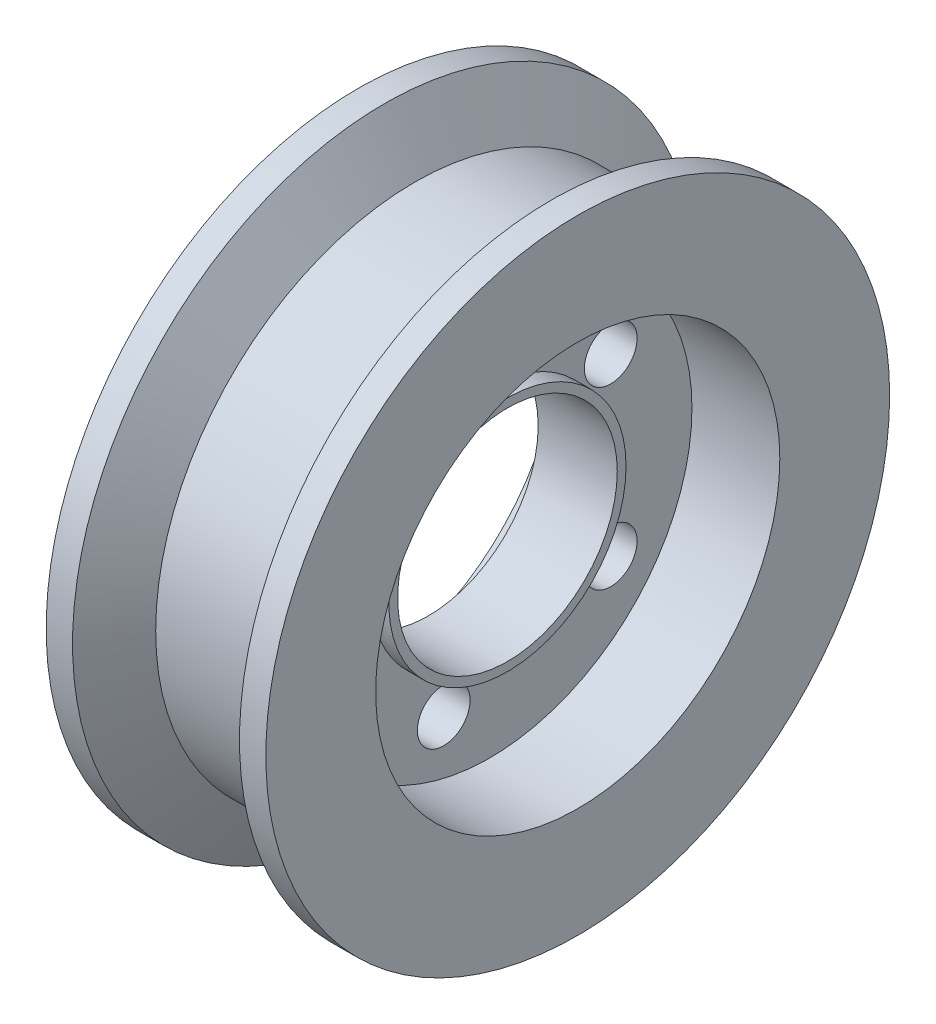
SolidWorks part; units mm, degrees
ref_plane "Front Plane" through (0, 0, 0) normal (1, 0, 0) x (0, 1, 0)
ref_plane "Top Plane" through (0, 0, 0) normal (0, 0, 1) x (0, 1, 0)
ref_plane "Right Plane" through (0, 0, 0) normal (0, 1, 0) x (-1, 0, 0)
sketch "Sketch2" plane through (0, 0, 0) normal (1, 0, 0) x (0, 1, 0)
  circle A0 centre (0, 0) radius 35.5
  circle A1 centre (0, 0) radius 12.5
  dimension "D1" = 71
  dimension "D2" = 25
extrude "Boss-Extrude1" add sketch "Sketch2" along normal mid plane 25 contours A0 A1
sketch "Sketch4" plane through (12.5, 0, 0) normal (1, 0, 0) x (0, 1, 0)
  circle A0 centre (0, 0) radius 23
  circle A1 centre (0, 0) radius 35.5 construction
  dimension "D1" = 12.5
extrude "Cut-Extrude1" cut sketch "Sketch4" against normal blind 10 contours A0
mirror "Mirror1" about plane through (0, 0, 0) normal (1, 0, 0) of "Cut-Extrude1"
sketch "Sketch5" plane through (2.5, 0, 0) normal (1, 0, 0) x (0, 1, 0)
  circle A0 centre (0, 17) radius 3
  dimension "D1" = 6
  dimension "D2" = 17
extrude "Cut-Extrude2" cut sketch "Sketch5" against normal through all
pattern_circular "CirPattern1" count 5 over 360 about axis through (0, 0, 0) along (1, 0, 0) of "Cut-Extrude2"
sketch "Sketch6" plane through (2.5, 0, 0) normal (1, 0, 0) x (0, 1, 0)
  circle A0 centre (0, 0) radius 12.5 construction
  circle A1 centre (0, 0) radius 12.5
  circle A2 centre (0, 0) radius 13.5
extrude "Boss-Extrude2" add sketch "Sketch6" along normal blind 2 and the other way blind 7
sketch "Sketch7" plane through (0, 0, 0) normal (0, 0, 1) x (0, 1, 0)
  line L0 (0, 0) -> (0, 30.7152) construction
  line L1 (-35.5, 9.5) -> (-29.5, 6.0359)
  line L2 (-35.5, 12.5) -> (-35.5, -12.5) construction
  line L3 (-29.5, 6.0359) -> (-29.5, -6.0359)
  line L4 (-29.5, -6.0359) -> (-35.5, -9.5)
  line L5 (-35.5, -9.5) -> (-35.5, 9.5)
  dimension "D1" = 3
  dimension "D2" = 3
  dimension "D3" = 6
  dimension "D4" = 60
  dimension "D5" = 60
revolve "Cut-Revolve1" cut sketch "Sketch7" angle 360 about L0
